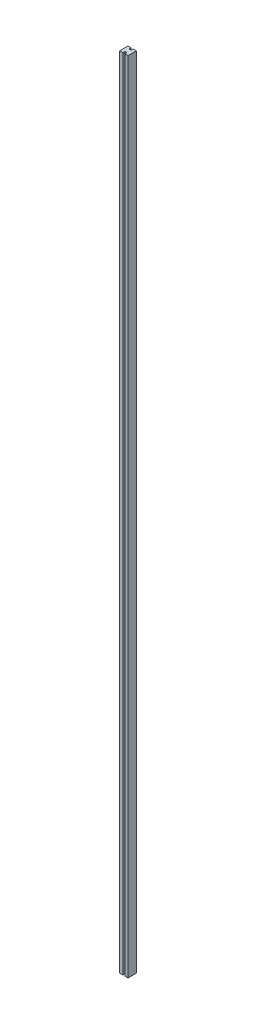
SolidWorks part; units mm, degrees
material "Acero inoxidable al cromo"
ref_plane "Front" through (0, 0, 0) normal (0, 0, 1) x (1, 0, 0)
ref_plane "Top" through (0, 0, 0) normal (0, 1, 0) x (1, 0, 0)
ref_plane "Right" through (0, 0, 0) normal (1, 0, 0) x (0, 0, -1)
sketch "Croquis1" plane through (0, 0, 0) normal (0, 1, 0) x (1, 0, 0)
  line L0 (0, 0) -> (7.65, 0)
  line L1 (7.65, 0) -> (7.65, -5)
  line L2 (7.65, -5) -> (12.65, -5)
  line L3 (12.65, -5) -> (12.65, 0)
  line L4 (12.65, 0) -> (20.3, 0)
  line L5 (20.3, 0) -> (20.3, -20.3)
  line L6 (20.3, -20.3) -> (12.65, -20.3)
  line L7 (12.65, -20.3) -> (12.65, -15.3)
  line L8 (12.65, -15.3) -> (7.65, -15.3)
  line L9 (7.65, -15.3) -> (7.65, -20.3)
  line L10 (7.65, -20.3) -> (0, -20.3)
  line L11 (0, -20.3) -> (0, 0)
  dimension "D1" = 20.3
  dimension "D2" = 20.3
  dimension "D3" = 5
  dimension "D4" = 5
extrude "Saliente-Extruir1" add sketch "Croquis1" along normal mid plane 1950
sketch "Croquis2" plane through (0, 975, 0) normal (0, 1, 0) x (1, 0, 0)
  line L0 (0, -10.15) -> (20.3, -10.15) construction
  line L1 (0, 0) -> (0, -20.3) construction
  line L2 (20.3, -20.3) -> (20.3, 0) construction
  circle A0 centre (10.15, -10.15) radius 2.2
  dimension "D1" = 4.4
extrude "Cortar-Extruir1" [suppressed] cut sketch "Croquis2" against normal blind 10
thread "Rosca1" [suppressed] pitch 0.7 start angle 0, offset 1, length 10, pitch 0.7, diameter 4.4
ref_plane "Plano1" through (7.95, 976, 10.15) normal (0, 0, 1) x (-1, 0, 0)
sketch "Perfil de rosca1" plane through (7.95, 976, 10.15) normal (0, 0, 1) x (-1, 0, 0)
  line L0 (0, 0) -> (0, 0.7) construction
  line L1 (0, 0) -> (0.3789, 0.2187)
  line L2 (0.3789, 0.2187) -> (0.3789, 0.3062)
  line L3 (0.3789, 0.3062) -> (0, 0.525)
  line L4 (0.3789, 0.2625) -> (0, 0.2625) construction
  line L11 (0, 0) -> (0, 0.525)
  point P2 (0, 0)
  dimension "Pitch" = 0.7
  dimension "Profile_Angle" = 60
  dimension "Profile_Land" = 0.0875
  dimension "Profile_Height" = 0.3789
mirror "Simetría2" [suppressed] about plane through (0, 0, 0) normal (0, 1, 0)
chamfer "Chaflán1" [suppressed] distance 1 angle 45
